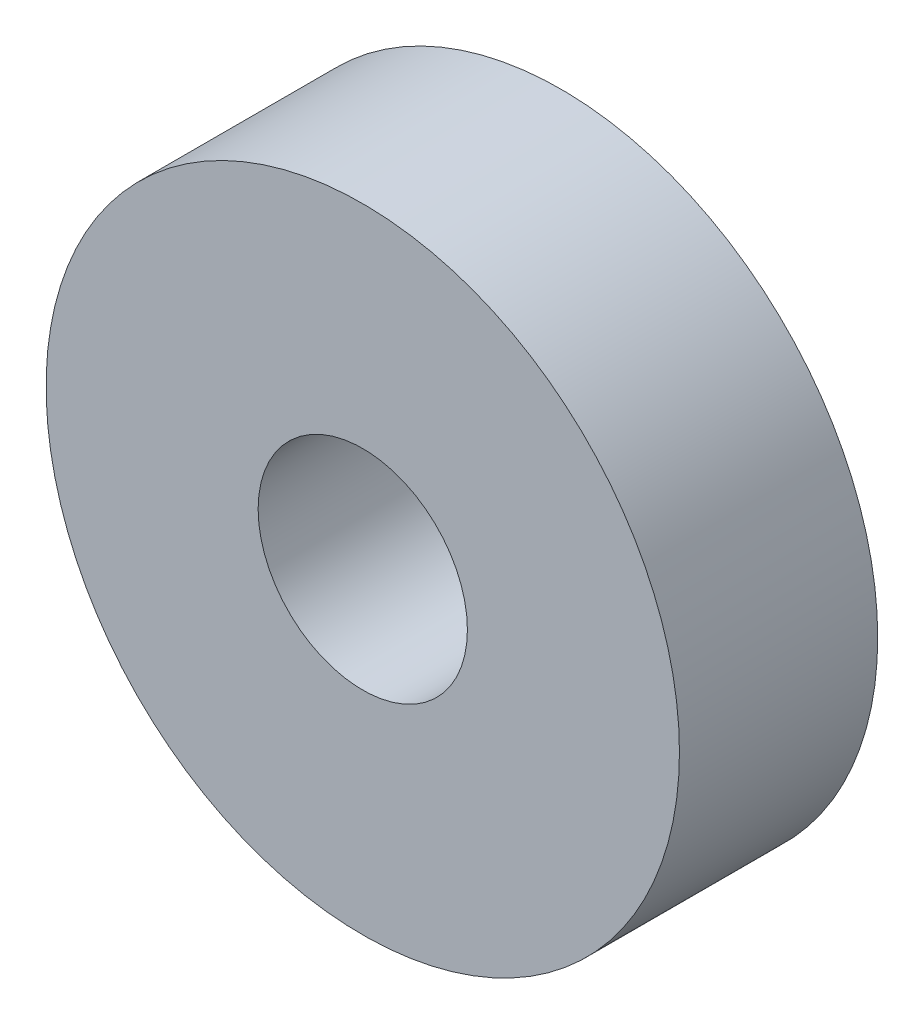
SolidWorks part; units mm, degrees
ref_plane "Ön Düzlem" through (0, 0, 0) normal (0, 0, 1) x (1, 0, 0)
ref_plane "Üst Düzlem" through (0, 0, 0) normal (0, 1, 0) x (1, 0, 0)
ref_plane "Sağ Düzlem" through (0, 0, 0) normal (1, 0, 0) x (0, 0, -1)
sketch "Çizim1" plane through (0, 0, 0) normal (0, 0, 1) x (1, 0, 0)
  circle A0 centre (0, 0) radius 11.5
  circle A1 centre (0, 0) radius 3.8
extrude "Yükseklik-Ekstrüzyon1" add sketch "Çizim1" along normal blind 7.2
